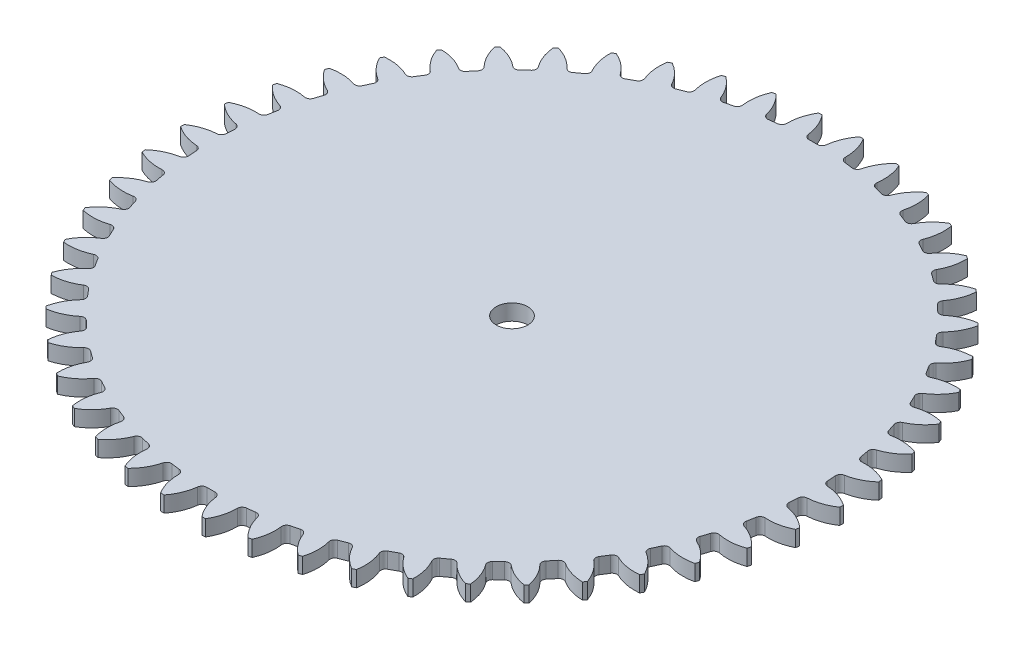
SolidWorks part; units mm, degrees
ref_plane "Front Plane" through (0, 0, 0) normal (0, 0, 1) x (1, 0, 0)
ref_plane "Top Plane" through (0, 0, 0) normal (0, 1, 0) x (1, 0, 0)
ref_plane "Right Plane" through (0, 0, 0) normal (1, 0, 0) x (0, 0, -1)
sketch "Sketch1" plane through (0, 0, 0) normal (0, 1, 0) x (1, 0, 0)
  circle A0 centre (0, 0) radius 5
  circle A1 centre (0, 0) radius 104
  dimension "D1" = 10
  dimension "D2" = 208
extrude "Boss-Extrude1" add sketch "Sketch1" along normal blind 5
sketch "Sketch2" plane through (0, 5, 0) normal (0, 1, 0) x (1, 0, 0)
  line L0 (0, 0) -> (0, 104) construction
  line L1 (-2.7398, 94.9605) -> (0, 0) construction
  line L2 (0, 89.6609) -> (-5.1722, 103.8713) construction
  circle A0 centre (0, 0) radius 104 construction
  arc A1 (2.7398, 94.9605) -> (-2.7398, 94.9605) centre (0, 0) ccw
  arc A2 (3.7407, 99.93) -> (-3.7407, 99.93) centre (0, 0) ccw construction
  arc A3 (5.9676, 103.8286) -> (-5.9676, 103.8286) centre (0, 0) ccw
  arc A4 (-5.9676, 103.8286) -> (-2.7398, 94.9605) centre (-17.7241, 94.5282) cw
  arc A5 (5.9676, 103.8286) -> (2.7398, 94.9605) centre (17.7241, 94.5282) ccw
  point P5 (-1.8171, 19.8426)
  point P6 (0, 0)
  point P16 (-3.6376, 99.6552)
  dimension "D1" = 208
  dimension "D2" = 200
  dimension "D3" = 9
  dimension "D4" = 20
  dimension "D5" = 7.4832
extrude "Cut-Extrude1" cut sketch "Sketch2" against normal through all
fillet "Fillet1" radius 1.52 2 edges at (2.7398, 2.5, -94.9605) (-2.7398, 2.5, -94.9605)
pattern_circular "CirPattern2" count 50 over 360 about axis through (0, 0, 0) along (0, 1, 0) of "Cut-Extrude1", "Fillet1"
equation "\"Module\" = 4"
equation "\"No. of Teeth\"= 50"
equation "\"Bore Diameter\" = 10"
equation "\"Pressure Angle\" = 20deg"
equation "\"Outer Diameter\"= ( \"No. of Teeth\" + 2 ) * \"Module\""
equation "\"Pitch Diameter\"= \"No. of Teeth\" * \"Module\""
equation "\"Backlash\"= 0.3 * \"Module\""
equation "\"Arc Length\" = ( \"Module\" * pi ) / 2 + \"Backlash\""
equation "\"Fillet Radius\"= .38 * \"Module\""
equation "\"Tooth Depth\"= IIF ( \"Module\" <= 1.25 , 2.4 * \"Module\" , 2.25 * \"Module\" )"
equation "\"D1@Sketch1\"=\"Bore Diameter\""
equation "\"D2@Sketch1\"=\"Outer Diameter\""
equation "\"D2@Sketch2\"=\"Pitch Diameter\""
equation "\"D1@Sketch2\"=\"Outer Diameter\""
equation "\"D3@Sketch2\"=\"Tooth Depth\""
equation "\"D4@Sketch2\"=\"Pressure Angle\""
equation "\"D5@Sketch2\"=\"Arc Length\""
equation "\"D1@Fillet1\"=\"Fillet Radius\""
equation "\"D1@CirPattern2\"=\"No. of Teeth\""
